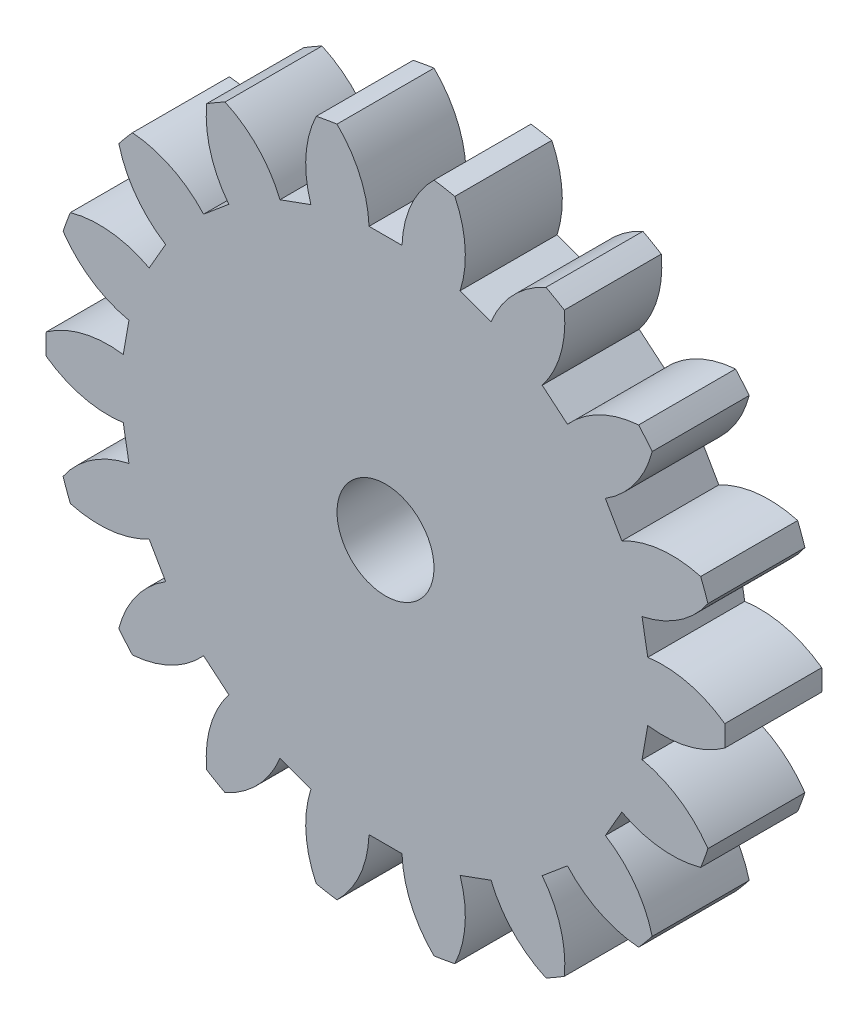
SolidWorks part; units mm, degrees
ref_plane "Front Plane" through (0, 0, 0) normal (0, 0, 1) x (1, 0, 0)
ref_plane "Top Plane" through (0, 0, 0) normal (0, 1, 0) x (1, 0, 0)
ref_plane "Right Plane" through (0, 0, 0) normal (1, 0, 0) x (0, 0, -1)
sketch "Sketch1" plane through (0, 0, 0) normal (0, 0, 1) x (1, 0, 0)
  circle A0 centre (0, 0) radius 35
  dimension "D1" = 70
extrude "Boss-Extrude1" add sketch "Sketch1" along normal blind 10
sketch "Sketch2" plane through (0, 0, 0) normal (0, 0, 1) x (1, 0, 0)
  line L0 (0, 0) -> (0, 43.5159) construction
  line L4 (0, 27.161) -> (-1.7, 27.161)
  line L5 (0, 27.161) -> (1.7, 27.161)
  arc A1 (-5, 34.641) -> (0, 37.0793) centre (-1.125, 33.0405) cw
  circle A12 centre (0, 0) radius 35 construction
  arc A13 (-5, 34.641) -> (-1.7, 27.161) centre (-12.6922, 26.7795) cw
  arc A14 (5, 34.641) -> (1.7, 27.161) centre (12.6922, 26.7795) ccw
  arc A15 (5, 34.641) -> (0, 37.0793) centre (1.125, 33.0405) ccw
  point P8 (-0.85, 27.161)
  dimension "D1" = 5
  dimension "D2" = 7.48
  dimension "D3" = 1.7
extrude "Cut-Extrude1" cut sketch "Sketch2" along normal blind 10
pattern_circular "CirPattern1" count 18 every 20 about axis through (0, 0, 0) along (0, 0, 1) of "Cut-Extrude1"
sketch "Sketch3" plane through (0, 0, 0) normal (0, 0, 1) x (1, 0, 0)
  circle A0 centre (0, 0) radius 5
  dimension "D1" = 10
extrude "Cut-Extrude2" cut sketch "Sketch3" along normal blind 10
